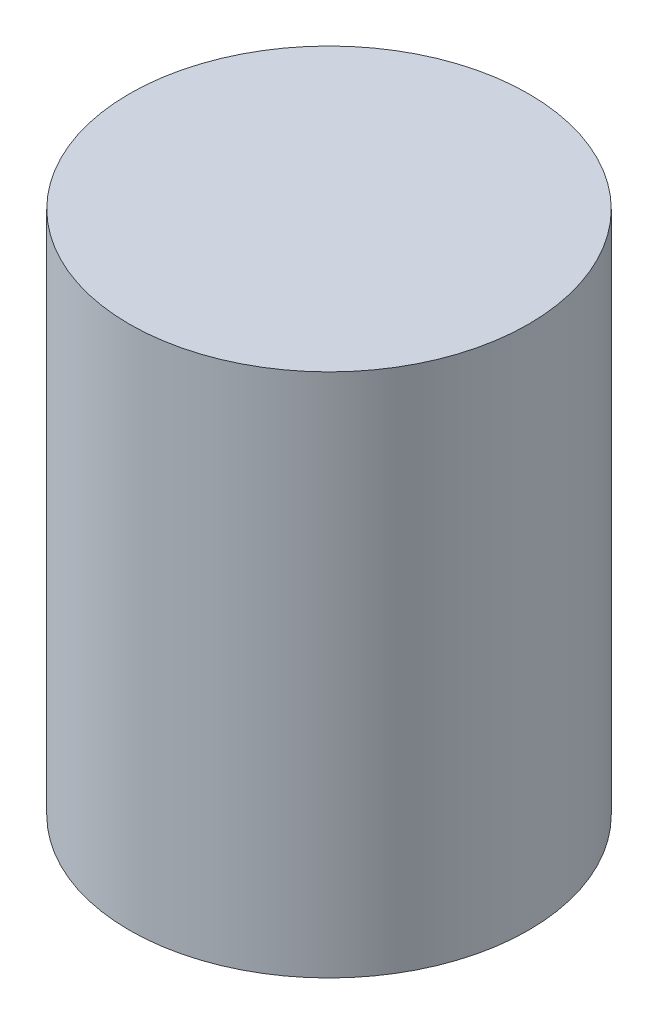
SolidWorks part; units mm, degrees
ref_plane "Front Plane" through (0, 0, 0) normal (0, 0, 1) x (1, 0, 0)
ref_plane "Top Plane" through (0, 0, 0) normal (0, 1, 0) x (1, 0, 0)
ref_plane "Right Plane" through (0, 0, 0) normal (1, 0, 0) x (0, 0, -1)
sketch "Sketch1" plane through (0, 0, 0) normal (0, 1, 0) x (1, 0, 0)
  circle A0 centre (0, 0) radius 3.175
  dimension "D1" = 6.35
extrude "Boss-Extrude1" add sketch "Sketch1" along normal blind 8.35
